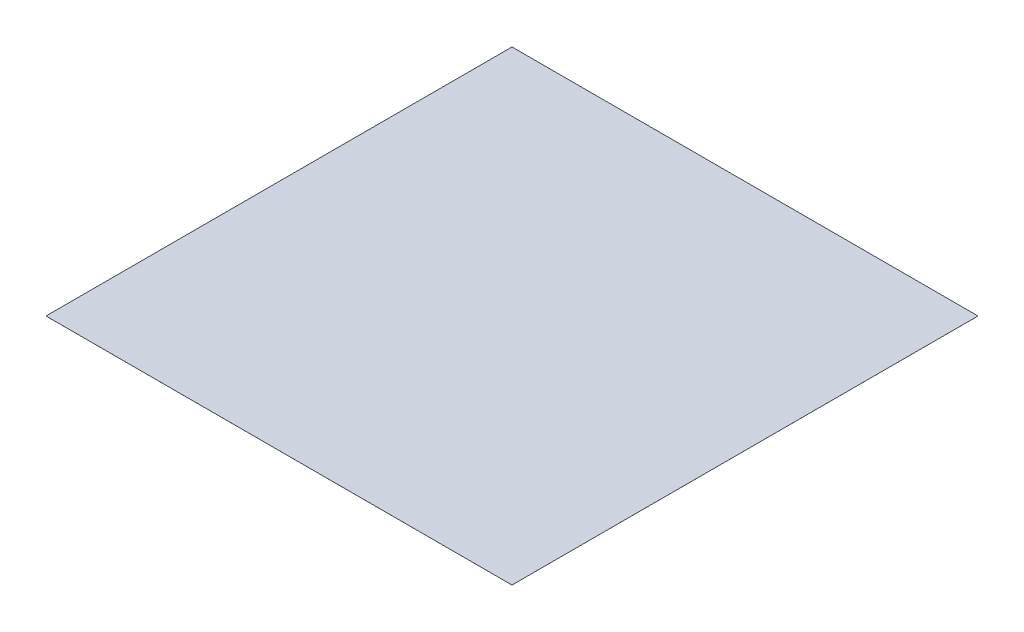
SolidWorks part; units mm, degrees
ref_plane "Front Plane" through (0, 0, 0) normal (0, 0, 1) x (1, 0, 0)
ref_plane "Top Plane" through (0, 0, 0) normal (0, 1, 0) x (1, 0, 0)
ref_plane "Right Plane" through (0, 0, 0) normal (1, 0, 0) x (0, 0, -1)
sketch "Sketch1" plane through (0, 0, 0) normal (0, 1, 0) x (1, 0, 0)
  line L1 (1500, -1500) -> (-1500, -1500)
  line L2 (1500, -1500) -> (1500, 1500)
  line L3 (1500, 1500) -> (-1500, 1500)
  line L4 (-1500, -1500) -> (-1500, 1500)
  line L5 (1500, -1500) -> (-1500, 1500) construction
  line L6 (1500, 1500) -> (-1500, -1500) construction
  point P0 (0, 0)
  dimension "D1" = 3000
  dimension "D2" = 3000
extrude "Boss-Extrude1" add sketch "Sketch1" along normal blind 0.1
